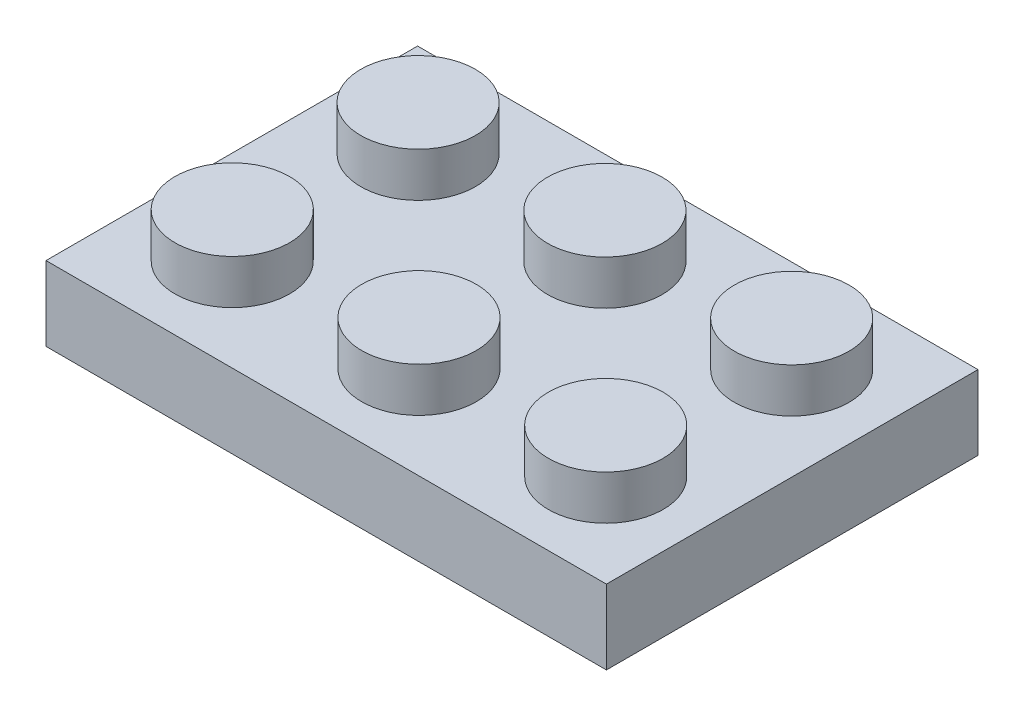
SolidWorks part; units mm, degrees
ref_plane "Front Plane" through (0, 0, 0) normal (0, 0, 1) x (1, 0, 0)
ref_plane "Top Plane" through (0, 0, 0) normal (0, 1, 0) x (1, 0, 0)
ref_plane "Right Plane" through (0, 0, 0) normal (1, 0, 0) x (0, 0, -1)
sketch "Sketch1" plane through (0, 0, 0) normal (0, 1, 0) x (1, 0, 0)
  line L1 (-11.945, 7.92) -> (11.945, 7.92)
  line L2 (-11.945, 7.92) -> (-11.945, -7.92)
  line L3 (-11.945, -7.92) -> (11.945, -7.92)
  line L4 (11.945, 7.92) -> (11.945, -7.92)
  line L5 (-11.945, 7.92) -> (11.945, -7.92) construction
  line L6 (-11.945, -7.92) -> (11.945, 7.92) construction
  point P0 (0, 0)
  dimension "D1" = 15.84
  dimension "D2" = 23.89
extrude "Boss-Extrude1" add sketch "Sketch1" against normal blind 3.17
sketch "Sketch2" plane through (0, 0, 0) normal (0, 1, 0) x (1, 0, 0)
  line L1 (11.945, 7.92) -> (-11.945, 7.92) construction
  line L2 (-11.945, 7.92) -> (-11.945, -7.92) construction
  line L3 (-11.945, -7.92) -> (11.945, -7.92) construction
  circle A0 centre (-7.9633, 3.96) radius 2.445
  circle A1 centre (0, 3.96) radius 2.445
  circle A2 centre (7.9633, 3.96) radius 2.445
  circle A3 centre (-7.965, -3.96) radius 2.445
  circle A4 centre (-0.005, -3.96) radius 2.445
  circle A5 centre (7.955, -3.96) radius 2.445
  dimension "D1" = 4.89
  dimension "D2" = 3.96
  dimension "D4" = 3.9817
  dimension "D5" = 7.9633
  dimension "D6" = 4.89
  dimension "D8" = 3.98
  dimension "D10" = 7.96
  dimension "D3" = 3
  dimension "D7" = 3.96
  dimension "D9" = 3
extrude "Boss-Extrude2" add sketch "Sketch2" along normal blind 1.89
shell "Shell1" thickness 0.8
sketch "Sketch3" plane through (0, -0.8, 0) normal (0, -1, 0) x (1, 0, 0)
  line L0 (11.945, 7.92) -> (11.945, -7.92) construction
  line L1 (11.945, -7.92) -> (-11.945, -7.92) construction
  line L3 (-11.945, -7.92) -> (-11.945, 7.92) construction
  circle A0 centre (3.9817, 0) radius 2.975
  circle A1 centre (-3.9817, 0) radius 2.975
  circle A3 centre (3.9817, 0) radius 2.83
  circle A4 centre (-3.9817, 0) radius 2.83
  dimension "D1" = 5.95
  dimension "D2" = 7.92
  dimension "D3" = 7.9633
  dimension "D5" = 7.9633
  dimension "D6" = 5.66
  dimension "D8" = 7.9633
  dimension "D4" = 2
  dimension "D7" = 2
extrude "Boss-Extrude3" add sketch "Sketch3" along normal blind 1.47
